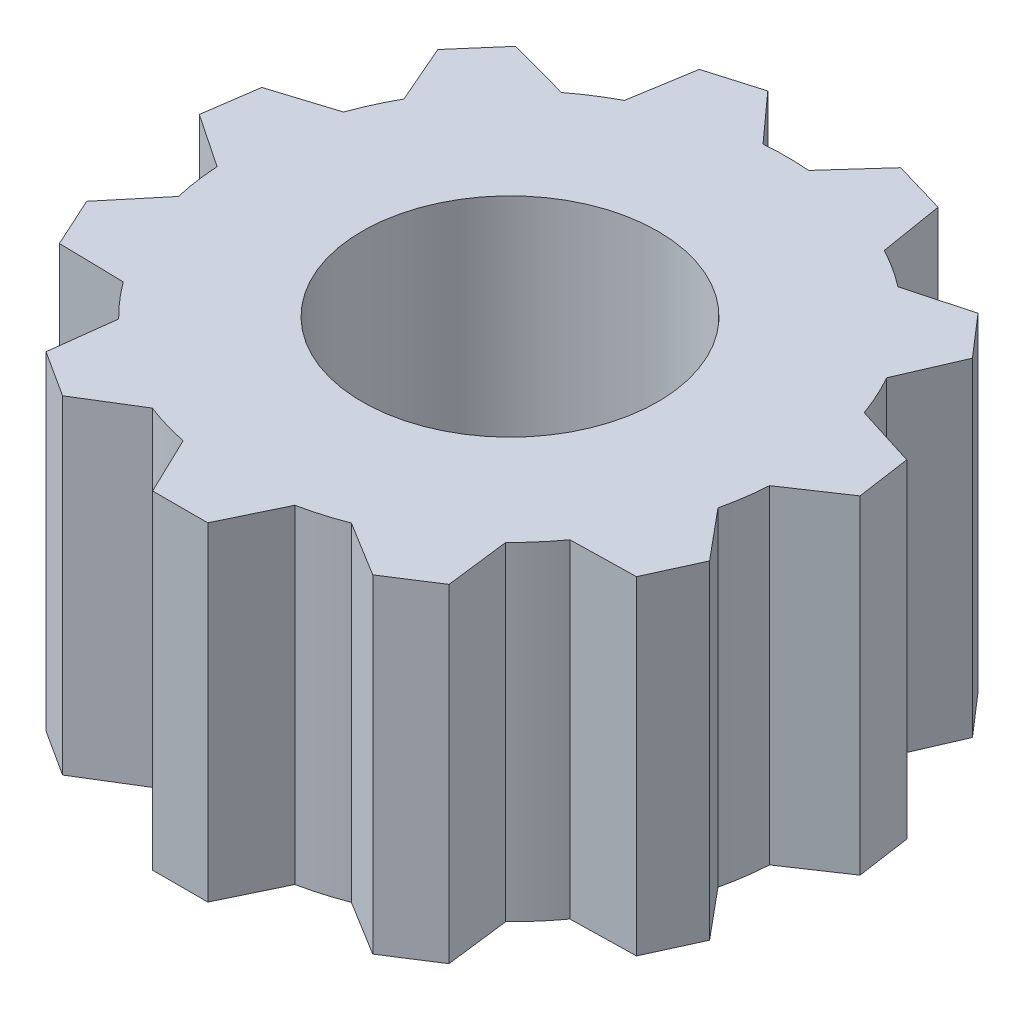
SolidWorks part; units mm, degrees
ref_plane "Front Plane" through (0, 0, 0) normal (0, 0, 1) x (1, 0, 0)
ref_plane "Top Plane" through (0, 0, 0) normal (0, 1, 0) x (1, 0, 0)
ref_plane "Right Plane" through (0, 0, 0) normal (1, 0, 0) x (0, 0, -1)
sketch "Sketch1" plane through (0, 0, 0) normal (0, 1, 0) x (1, 0, 0)
  circle A0 centre (0, 0) radius 4.5
  dimension "D1" = 9
extrude "Boss-Extrude1" add sketch "Sketch1" along normal blind 5
ref_plane "Plane2" through (0, 5, 0) normal (0, -1, 0) x (-1, 0, 0)
sketch "Sketch12" plane through (0, 5, 0) normal (0, -1, 0) x (-1, 0, 0)
  circle A0 centre (0, 0) radius 4.5 construction
  circle A2 centre (0, 0) radius 12.5 construction
  circle A3 centre (0, 0) radius 8.425
  circle A4 centre (0, 0) radius 10.5 construction
  circle A5 centre (0, 0) radius 4.5
  dimension "D1" = 16.85
  dimension "D2" = 21
  dimension "D3" = 25
extrude "Boss-Extrude6" add sketch "Sketch12" along normal blind 5 separate body
sketch "Sketch13" plane through (0, 0, 0) normal (0, -1, 0) x (1, 0, 0)
  line L0 (0, 12.15) -> (0, -12.15) construction
  line L1 (-12.15, 0) -> (12.15, 0) construction
  line L2 (0.84, 10.0399) -> (1.7, 8.2517)
  line L3 (-0.84, 10.0399) -> (-1.7, 8.2517)
  line L4 (-0.84, 10.0399) -> (0.84, 10.0399)
  line L5 (-1.7, 8.2517) -> (3.0395, 8.082) construction
  circle A0 centre (0, 0) radius 10.075 construction
  circle A1 centre (0, 0) radius 12.15 construction
  circle A4 centre (0, 0) radius 8.425
  circle A5 centre (0, 0) radius 8.425
  circle A6 centre (0, 0) radius 8.425
  point P11 (0, 0)
  circle M1 centre (0, 0) radius 8.425
  dimension "D1" = 20.15
  dimension "D2" = 24.3
  dimension "D3" = 16.85
  dimension "D4" = 1.7
  dimension "D5" = 1.7
  dimension "D6" = 1.68
  dimension "D7" = 66.367
  dimension "D8" = 0
extrude "Boss-Extrude9" add sketch "Sketch13" against normal blind 5 separate body contours L4 L3 L2 M1
pattern_circular "CirPattern2" count 11 over 360 about axis through (0, 0, 0) along (0, 1, 0) of bodies 130
sketch "Sketch17" plane through (0, 0, 0) normal (0, -1, 0) x (1, 0, 0)
  line L0 (7.0376, -7.2096) -> (8.1377, -5.9399) construction
  line L1 (8.1377, -5.9399) -> (7.3495, -4.1189) construction
  line L2 (5.123, -6.6885) -> (7.0376, -7.2096) construction
  line L3 (2.0226, -9.8699) -> (3.6345, -9.3966) construction
  line L4 (3.6345, -9.3966) -> (3.9559, -7.4385) construction
  line L5 (0.6936, -8.3964) -> (2.0226, -9.8699) construction
  line L6 (-3.6345, -9.3966) -> (-2.0226, -9.8699) construction
  line L7 (-2.0226, -9.8699) -> (-0.6936, -8.3964) construction
  line L8 (-3.9559, -7.4385) -> (-3.6345, -9.3966) construction
  line L9 (-8.1377, -5.9399) -> (-7.0376, -7.2096) construction
  line L10 (-7.0376, -7.2096) -> (-5.123, -6.6885) construction
  line L11 (-7.3495, -4.1189) -> (-8.1377, -5.9399) construction
  line L12 (-10.0573, -0.5974) -> (-9.8182, -2.2603) construction
  line L13 (-9.8182, -2.2603) -> (-7.9258, -2.857) construction
  line L14 (-8.4096, 0.5084) -> (-10.0573, -0.5974) construction
  line L15 (-4.7213, 8.9003) -> (-6.1346, 7.992) construction
  line L16 (-6.1346, 7.992) -> (-5.8913, 6.0227) construction
  line L17 (-3.0311, 7.8609) -> (-4.7213, 8.9003) construction
  line L18 (-8.7837, 4.9348) -> (-9.4816, 3.4066) construction
  line L19 (-9.4816, 3.4066) -> (-8.2122, 1.8815) construction
  line L20 (-6.7998, 4.9743) -> (-8.7837, 4.9348) construction
  line L21 (9.8182, -2.2603) -> (10.0573, -0.5974) construction
  line L22 (10.0573, -0.5974) -> (8.4096, 0.5084) construction
  line L23 (7.9258, -2.857) -> (9.8182, -2.2603) construction
  line L24 (9.4816, 3.4066) -> (8.7837, 4.9348) construction
  line L25 (8.7837, 4.9348) -> (6.7998, 4.9743) construction
  line L26 (8.2122, 1.8815) -> (9.4816, 3.4066) construction
  line L27 (0.84, 10.0399) -> (-0.84, 10.0399) construction
  line L28 (-0.84, 10.0399) -> (-1.7, 8.2517) construction
  line L29 (1.7, 8.2517) -> (0.84, 10.0399) construction
  line L30 (7.0376, -7.2096) -> (8.1377, -5.9399)
  line L31 (8.1377, -5.9399) -> (7.3495, -4.1189)
  line L32 (5.123, -6.6885) -> (7.0376, -7.2096)
  line L33 (2.0226, -9.8699) -> (3.6345, -9.3966)
  line L34 (3.6345, -9.3966) -> (3.9559, -7.4385)
  line L35 (0.6936, -8.3964) -> (2.0226, -9.8699)
  line L36 (-3.6345, -9.3966) -> (-2.0226, -9.8699)
  line L37 (-2.0226, -9.8699) -> (-0.6936, -8.3964)
  line L38 (-3.9559, -7.4385) -> (-3.6345, -9.3966)
  line L39 (-8.1377, -5.9399) -> (-7.0376, -7.2096)
  line L40 (-7.0376, -7.2096) -> (-5.123, -6.6885)
  line L41 (-7.3495, -4.1189) -> (-8.1377, -5.9399)
  line L42 (-10.0573, -0.5974) -> (-9.8182, -2.2603)
  line L43 (-9.8182, -2.2603) -> (-7.9258, -2.857)
  line L44 (-8.4096, 0.5084) -> (-10.0573, -0.5974)
  line L45 (-4.7213, 8.9003) -> (-6.1346, 7.992)
  line L46 (-6.1346, 7.992) -> (-5.8913, 6.0227)
  line L47 (-3.0311, 7.8609) -> (-4.7213, 8.9003)
  line L48 (-8.7837, 4.9348) -> (-9.4816, 3.4066)
  line L49 (-9.4816, 3.4066) -> (-8.2122, 1.8815)
  line L50 (-6.7998, 4.9743) -> (-8.7837, 4.9348)
  line L51 (9.8182, -2.2603) -> (10.0573, -0.5974)
  line L52 (10.0573, -0.5974) -> (8.4096, 0.5084)
  line L53 (7.9258, -2.857) -> (9.8182, -2.2603)
  line L54 (9.4816, 3.4066) -> (8.7837, 4.9348)
  line L55 (8.7837, 4.9348) -> (6.7998, 4.9743)
  line L56 (8.2122, 1.8815) -> (9.4816, 3.4066)
  line L57 (0.84, 10.0399) -> (-0.84, 10.0399)
  line L58 (-0.84, 10.0399) -> (-1.7, 8.2517)
  line L59 (1.7, 8.2517) -> (0.84, 10.0399)
  arc A0 (5.123, -6.6885) -> (7.3495, -4.1189) centre (0, 0) ccw construction
  arc A1 (0.6936, -8.3964) -> (3.9559, -7.4385) centre (0, 0) ccw construction
  arc A2 (-3.9559, -7.4385) -> (-0.6936, -8.3964) centre (0, 0) ccw construction
  arc A4 (-7.3495, -4.1189) -> (-5.123, -6.6885) centre (0, 0) ccw construction
  arc A5 (-8.4096, 0.5084) -> (-7.9258, -2.857) centre (0, 0) ccw construction
  arc A6 (-3.0311, 7.8609) -> (-5.8913, 6.0227) centre (0, 0) ccw construction
  arc A7 (-6.7998, 4.9743) -> (-8.2122, 1.8815) centre (0, 0) ccw construction
  arc A8 (7.9258, -2.857) -> (8.4096, 0.5084) centre (0, 0) ccw construction
  arc A9 (8.2122, 1.8815) -> (6.7998, 4.9743) centre (0, 0) ccw construction
  arc A10 (1.7, 8.2517) -> (-1.7, 8.2517) centre (0, 0) ccw construction
  circle A11 centre (0, 0) radius 8.425 construction
  arc A12 (5.123, -6.6885) -> (7.3495, -4.1189) centre (0, 0) ccw
  arc A13 (0.6936, -8.3964) -> (3.9559, -7.4385) centre (0, 0) ccw
  arc A14 (-3.9559, -7.4385) -> (-0.6936, -8.3964) centre (0, 0) ccw
  arc A15 (-7.3495, -4.1189) -> (-5.123, -6.6885) centre (0, 0) ccw
  arc A16 (-8.4096, 0.5084) -> (-7.9258, -2.857) centre (0, 0) ccw
  arc A17 (-3.0311, 7.8609) -> (-5.8913, 6.0227) centre (0, 0) ccw
  arc A18 (-6.7998, 4.9743) -> (-8.2122, 1.8815) centre (0, 0) ccw
  arc A19 (7.9258, -2.857) -> (8.4096, 0.5084) centre (0, 0) ccw
  arc A20 (8.2122, 1.8815) -> (6.7998, 4.9743) centre (0, 0) ccw
  arc A21 (1.7, 8.2517) -> (-1.7, 8.2517) centre (0, 0) ccw
  circle A22 centre (0, 0) radius 8.425
  circle M1 centre (0, 0) radius 8.425
  circle M2 centre (0, 0) radius 4.5
  dimension "D1" = 6.0622
other "AlignGroup1"
other "AlignGroup2"
extrude "Boss-Extrude10" add sketch "Sketch17" along normal blind 5 contours M1 M2 | L59 L57 L58 M1 | L47 L45 L46 M1 | L50 L48 L49 M1 | L44 L42 L43 M1 | L41 L39 L40 M1 | L38 L36 L37 M1 | L35 L33 L34 M1 | L32 L30 L31 M1 | L53 L51 L52 M1 | L56 L54 L55 M1
sketch "Sketch18" plane through (0, 0, 0) normal (0, -1, 0) x (1, 0, 0)
  line L3 (6.1346, 7.992) -> (4.7213, 8.9003)
  line L4 (4.7213, 8.9003) -> (3.0311, 7.8609)
  line L5 (5.8913, 6.0227) -> (6.1346, 7.992)
  line L6 (6.1346, 7.992) -> (4.7213, 8.9003)
  line L7 (4.7213, 8.9003) -> (3.0311, 7.8609)
  line L8 (5.8913, 6.0227) -> (6.1346, 7.992)
  arc A1 (5.8913, 6.0227) -> (3.0311, 7.8609) centre (0, 0) ccw
  arc A6 (5.8913, 6.0227) -> (3.0311, 7.8609) centre (0, 0) ccw
  dimension "D1" = 0
extrude "Boss-Extrude11" add sketch "Sketch18" along normal blind 5
sketch "Sketch19" plane through (0, 0, 0) normal (0, -1, 0) x (1, 0, 0)
  circle A1 centre (0, 0) radius 4.5
  circle A2 centre (0, 0) radius 4.5
  dimension "D1" = 0
extrude "Cut-Extrude1" cut sketch "Sketch19" against normal blind 10
